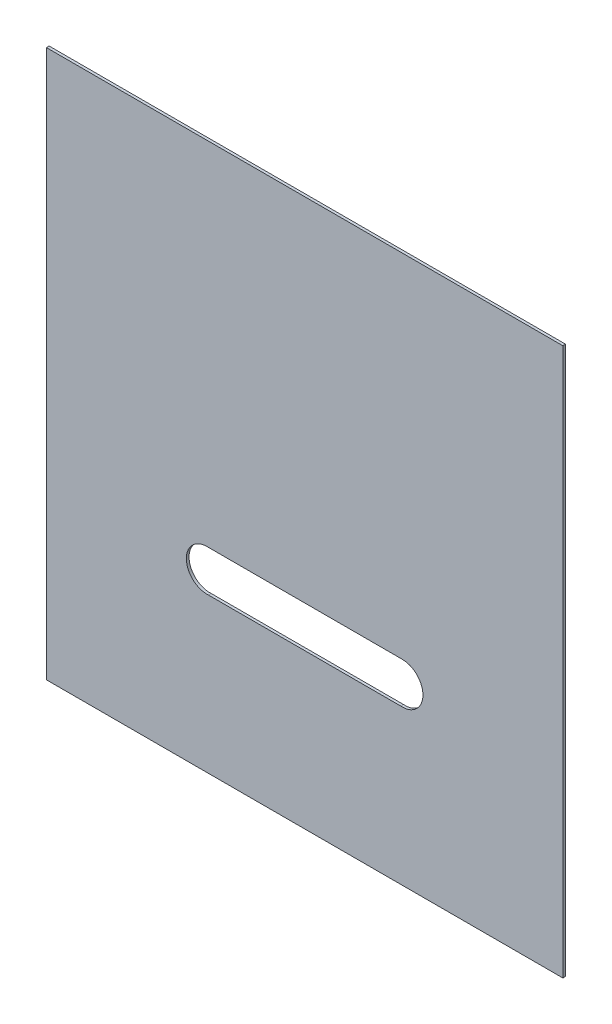
SolidWorks part; units mm, degrees
ref_plane "Front Plane" through (0, 0, 0) normal (0, 0, 1) x (1, 0, 0)
ref_plane "Top Plane" through (0, 0, 0) normal (0, 1, 0) x (1, 0, 0)
ref_plane "Right Plane" through (0, 0, 0) normal (1, 0, 0) x (0, 0, -1)
ref_plane "Plane1" through (0, 0, 0) normal (0, 0, -1) x (-1, 0, 0)
sketch "Sketch1" plane through (0, 0, 0) normal (0, 0, -1) x (-1, 0, 0)
  line L0 (191, 225) -> (-191, 225)
  line L1 (-191, 225) -> (-191, -180)
  line L2 (-191, -180) -> (191, -180)
  line L3 (191, -180) -> (191, 225)
  point P5 (0, 225)
  dimension "D1" = 382
  dimension "D2" = 405
extrude "Boss-Extrude1" add sketch "Sketch1" against normal blind 2
sketch "Sketch4" plane through (0, 0, 2) normal (0, 0, 1) x (1, 0, 0)
  line L0 (-72.225, -50.5) -> (72.225, -50.5) construction
  line L1 (-72.225, -35.25) -> (72.225, -35.25)
  line L2 (-71.1205, -65.75) -> (72.225, -65.75)
  line L3 (191, -180) -> (-191, -180) construction
  line L4 (0, 0) -> (0, -54.3477) construction
  arc A2 (-71.1205, -65.75) -> (-72.225, -35.25) centre (-72.225, -50.52) cw
  arc A3 (71.1205, -65.75) -> (72.225, -35.25) centre (72.225, -50.52) ccw
  point P2 (0, -20)
  dimension "D6" = 15.27
  dimension "D1" = 129.5
  dimension "D2" = 144.45
  dimension "D3" = 72.225
  dimension "D4" = 30.5
  dimension "D5" = 15.25
extrude "Cut-Extrude2" cut sketch "Sketch4" against normal through all
